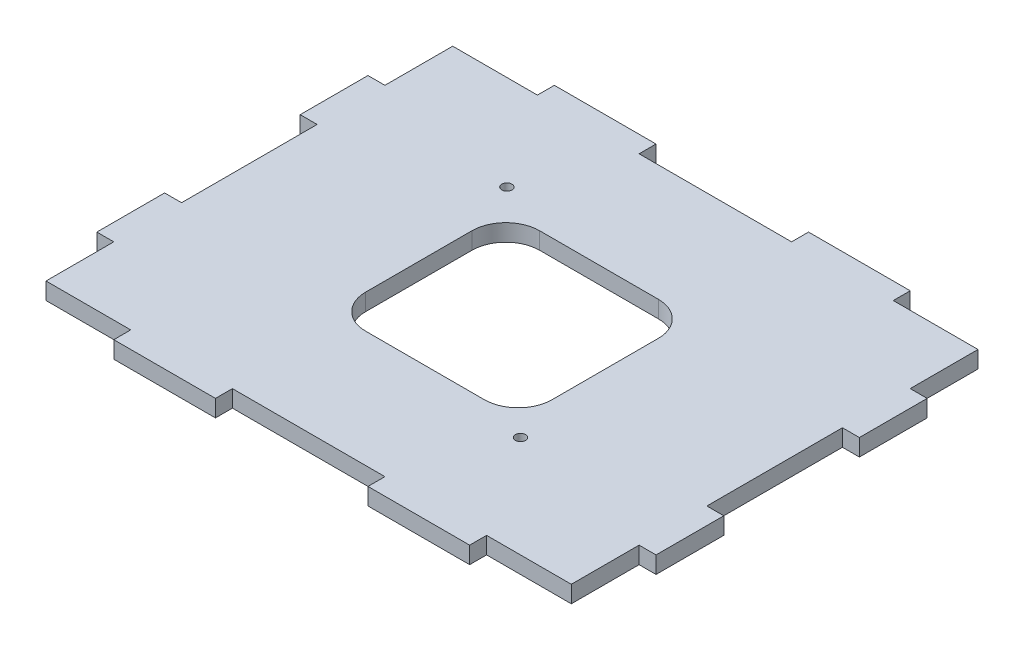
SolidWorks part; units mm, degrees
ref_plane "Front Plane" through (0, 0, 0) normal (0, 0, 1) x (1, 0, 0)
ref_plane "Top Plane" through (0, 0, 0) normal (0, 1, 0) x (1, 0, 0)
ref_plane "Right Plane" through (0, 0, 0) normal (1, 0, 0) x (0, 0, -1)
sketch "Sketch1" plane through (0, 0, 0) normal (0, 1, 0) x (1, 0, 0)
  line L0 (0, 39.5281) -> (0, -52.3915) construction
  line L1 (-81.7361, 0) -> (90.7338, 0) construction
  line L2 (-77.5, 60) -> (-52.5, 60)
  line L3 (-77.5, 60) -> (77.5, 60) construction
  line L4 (-77.5, 60) -> (-77.5, -60) construction
  line L5 (-77.5, -60) -> (77.5, -60) construction
  line L6 (77.5, 60) -> (77.5, -60) construction
  line L7 (-77.5, 60) -> (77.5, -60) construction
  line L8 (-77.5, -60) -> (77.5, 60) construction
  line L9 (-52.5, 60) -> (-52.5, 65)
  line L10 (-52.5, 65) -> (-22.5, 65)
  line L11 (-22.5, 65) -> (-22.5, 60)
  line L12 (-22.5, 60) -> (22.5, 60)
  line L13 (22.5, 65) -> (22.5, 60)
  line L14 (52.5, 65) -> (22.5, 65)
  line L15 (52.5, 60) -> (52.5, 65)
  line L16 (77.5, 60) -> (52.5, 60)
  line L17 (77.5, -60) -> (52.5, -60)
  line L18 (52.5, -60) -> (52.5, -65)
  line L19 (52.5, -65) -> (22.5, -65)
  line L20 (22.5, -65) -> (22.5, -60)
  line L21 (-22.5, -60) -> (22.5, -60)
  line L22 (-22.5, -65) -> (-22.5, -60)
  line L23 (-52.5, -65) -> (-22.5, -65)
  line L24 (-52.5, -60) -> (-52.5, -65)
  line L25 (-77.5, -60) -> (-52.5, -60)
  line L26 (-77.5, 60) -> (-77.5, 40)
  line L27 (-77.5, 40) -> (-82.5, 40)
  line L28 (-82.5, 40) -> (-82.5, 20)
  line L29 (-82.5, 20) -> (-77.5, 20)
  line L30 (-77.5, 20) -> (-77.5, -20)
  line L31 (-82.5, -20) -> (-77.5, -20)
  line L32 (-82.5, -40) -> (-82.5, -20)
  line L33 (-77.5, -40) -> (-82.5, -40)
  line L34 (-77.5, -60) -> (-77.5, -40)
  line L35 (77.5, -60) -> (77.5, -40)
  line L36 (77.5, -40) -> (82.5, -40)
  line L37 (82.5, -40) -> (82.5, -20)
  line L38 (82.5, -20) -> (77.5, -20)
  line L39 (77.5, 20) -> (77.5, -20)
  line L40 (82.5, 20) -> (77.5, 20)
  line L41 (82.5, 40) -> (82.5, 20)
  line L42 (77.5, 40) -> (82.5, 40)
  line L43 (77.5, 60) -> (77.5, 40)
  point P5 (0, 0)
  point P16 (0, 60)
  point P27 (0, -60)
  point P34 (-77.5, 0)
  point P45 (77.5, 0)
  dimension "D1" = 120
  dimension "D2" = 155
  dimension "D3" = 25
  dimension "D4" = 30
extrude "Boss-Extrude1" add sketch "Sketch1" along normal blind 5
sketch "Sketch3" plane through (0, 5, 0) normal (0, 1, 0) x (1, 0, 0)
  line L5 (37.5, -35) -> (-37.5, 35) construction
  line L6 (37.5, 35) -> (-37.5, -35) construction
  line L7 (17.5, -25.6667) -> (-17.5, -25.6667)
  line L8 (27.5, -15.6667) -> (27.5, 15.6667)
  line L9 (17.5, 25.6667) -> (-17.5, 25.6667)
  line L10 (-27.5, -15.6667) -> (-27.5, 15.6667)
  line L11 (27.5, -25.6667) -> (-27.5, 25.6667) construction
  line L12 (27.5, 25.6667) -> (-27.5, -25.6667) construction
  circle A0 centre (-33.5, 32) radius 1.5
  circle A1 centre (32.5, -30) radius 1.5
  arc A2 (17.5, 25.6667) -> (27.5, 15.6667) centre (17.5, 15.6667) cw
  arc A3 (27.5, -15.6667) -> (17.5, -25.6667) centre (17.5, -15.6667) cw
  arc A4 (-17.5, -25.6667) -> (-27.5, -15.6667) centre (-17.5, -15.6667) cw
  arc A5 (-27.5, 15.6667) -> (-17.5, 25.6667) centre (-17.5, 15.6667) cw
  point P0 (0, 0)
  point P6 (0, 0)
  point P27 (0, 0)
  dimension "D9" = 10
  dimension "D1" = 75
  dimension "D2" = 70
  dimension "D3" = 55
  dimension "D4" = 51.3333
extrude "Cut-Extrude3" cut sketch "Sketch3" against normal blind 10
